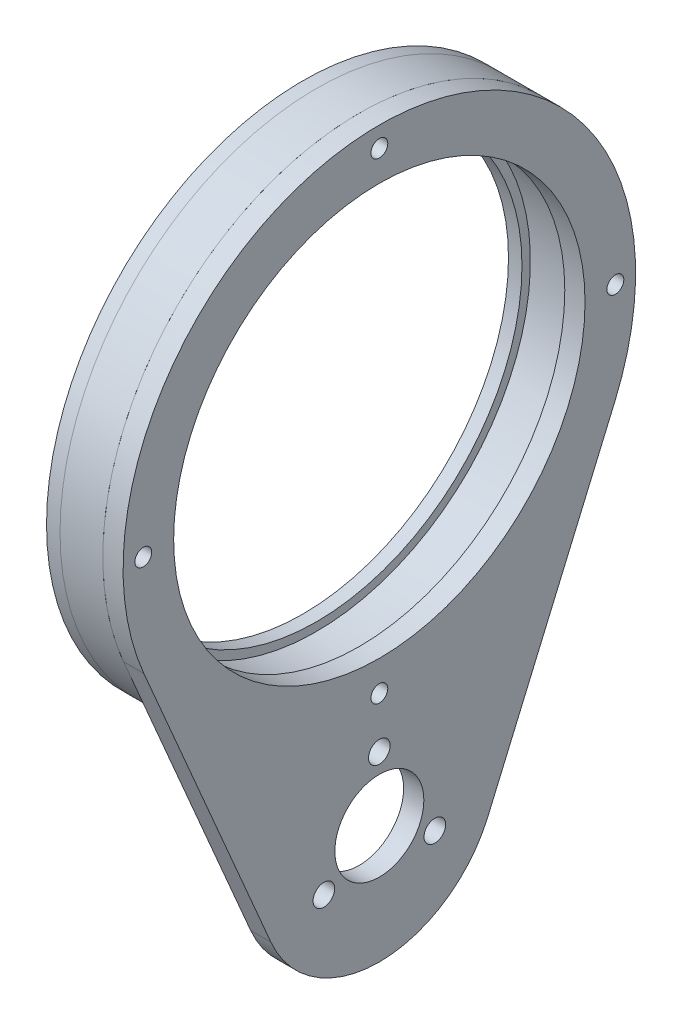
SolidWorks part; units mm, degrees
ref_plane "正面" through (0, 0, 0) normal (0, 0, 1) x (1, 0, 0)
ref_plane "平面" through (0, 0, 0) normal (0, 1, 0) x (1, 0, 0)
ref_plane "右側面" through (0, 0, 0) normal (1, 0, 0) x (0, 0, -1)
sketch "ｽｹｯﾁ2" plane through (0, 0, 0) normal (1, 0, 0) x (0, 0, -1)
  line L0 (0, 0) -> (0, 52) construction
  line L1 (-34.9224, 37.0192) -> (-16.0827, -6.899)
  line L2 (34.9224, 37.0192) -> (16.0827, -6.899)
  arc A0 (-16.0827, -6.899) -> (16.0827, -6.899) centre (0, 0) ccw
  arc A1 (34.9224, 37.0192) -> (-34.9224, 37.0192) centre (0, 52) ccw
  circle A2 centre (0, 0) radius 6.6
  circle A3 centre (0, 0) radius 9.5 construction
  circle A4 centre (0, 9.5) radius 1.6
  circle A5 centre (8.2272, -4.75) radius 1.6
  circle A6 centre (-8.2272, -4.75) radius 1.6
  circle A7 centre (0, 52) radius 30.5
  circle A8 centre (0, 52) radius 35 construction
  circle A9 centre (0, 87) radius 1.25
  circle A10 centre (0, 17) radius 1.25
  circle A11 centre (35, 52) radius 1.25
  circle A12 centre (-35, 52) radius 1.25
  point P17 (0, 0)
  dimension "D1" = 35
  dimension "D2" = 76
  dimension "D4" = 13.2
  dimension "D5" = 19
  dimension "D6" = 3.2
  dimension "D8" = 61
  dimension "D9" = 70
  dimension "D10" = 2.5
  dimension "D3" = 52
  dimension "D7" = 3
extrude "ﾎﾞｽ - 押し出し1" add sketch "ｽｹｯﾁ2" along normal blind 3
sketch "ｽｹｯﾁ6" plane through (0, 0, 0) normal (-1, 0, 0) x (0, 0, 1)
  circle A0 centre (0, 52) radius 38
  arc A2 (34.9224, 37.0192) -> (-34.9224, 37.0192) centre (0, 52) ccw construction
  circle A3 centre (0, 52) radius 31.75
  circle A4 centre (0, 87) radius 1.6
  circle A5 centre (35, 52) radius 1.6
  circle A6 centre (0, 17) radius 1.6
  circle A7 centre (-35, 52) radius 1.6
  point P10 (-55.209, 77.0157)
  point P11 (0, 0)
  point P12 (0, 0)
  point P19 (0, 52)
  dimension "D1" = 63.5
  dimension "D2" = 3.2
  dimension "D3" = 4
extrude "ﾎﾞｽ - 押し出し4" add sketch "ｽｹｯﾁ6" along normal blind 6.35 separate body
sketch "ｽｹｯﾁ7" plane through (-6.35, 0, 0) normal (-1, 0, 0) x (0, 0, 1)
  circle A0 centre (0, 52) radius 38 construction
  circle A1 centre (0, 52) radius 38
  circle A2 centre (0, 52) radius 30.5 construction
  circle A3 centre (0, 52) radius 30.5
  circle A4 centre (0, 17) radius 1.6 construction
  circle A5 centre (35, 52) radius 1.6 construction
  circle A6 centre (-35, 52) radius 1.6 construction
  circle A7 centre (0, 87) radius 1.6 construction
  circle A8 centre (0, 17) radius 1.6
  circle A9 centre (35, 52) radius 1.6
  circle A10 centre (-35, 52) radius 1.6
  circle A11 centre (0, 87) radius 1.6
extrude "ﾎﾞｽ - 押し出し5" add sketch "ｽｹｯﾁ7" along normal blind 2 separate body
